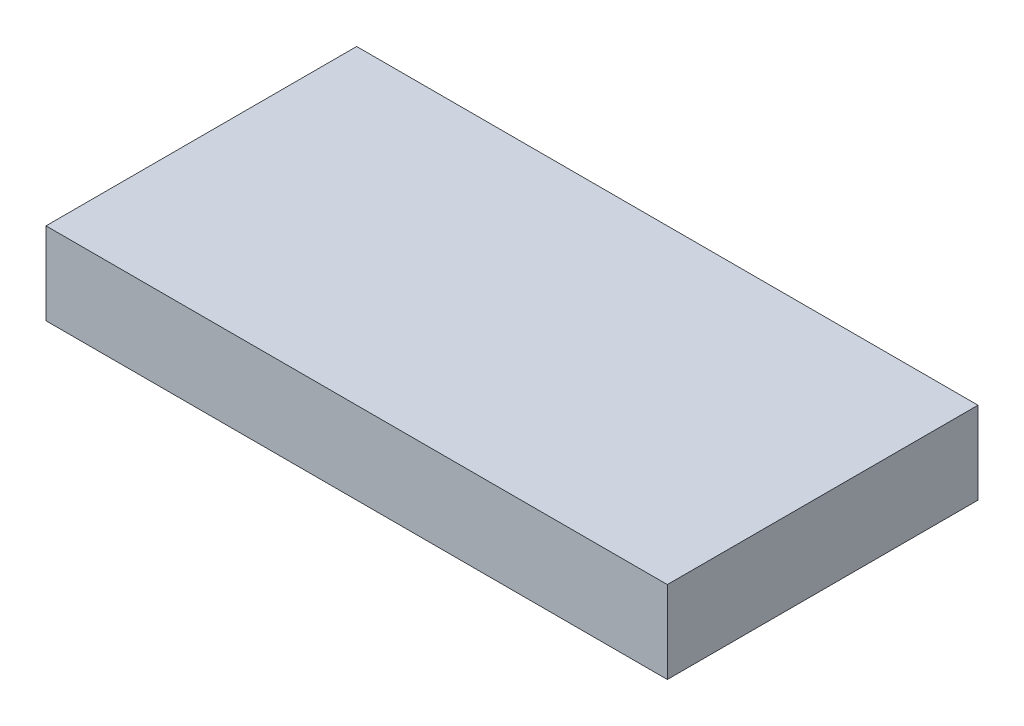
SolidWorks part; units mm, degrees
ref_plane "Front Plane" through (0, 0, 0) normal (0, 0, 1) x (1, 0, 0)
ref_plane "Top Plane" through (0, 0, 0) normal (0, 1, 0) x (1, 0, 0)
ref_plane "Right Plane" through (0, 0, 0) normal (1, 0, 0) x (0, 0, -1)
sketch "Sketch1" plane through (0, 0, 0) normal (0, 1, 0) x (1, 0, 0)
  line L1 (-215.9, -107.95) -> (215.9, -107.95)
  line L2 (-215.9, -107.95) -> (-215.9, 107.95)
  line L3 (-215.9, 107.95) -> (215.9, 107.95)
  line L4 (215.9, -107.95) -> (215.9, 107.95)
  line L5 (-215.9, -107.95) -> (215.9, 107.95) construction
  line L6 (-215.9, 107.95) -> (215.9, -107.95) construction
  point P0 (0, 0)
  dimension "D1" = 215.9
  dimension "D2" = 431.8
extrude "Boss-Extrude1" add sketch "Sketch1" along normal blind 57.15
sketch "Sketch2" plane through (0, 0, 0) normal (0, -1, 0) x (1, 0, 0)
  line L1 (-177.8, -69.85) -> (177.8, -69.85) construction
  line L2 (-177.8, -69.85) -> (-177.8, 69.85) construction
  line L3 (-177.8, 69.85) -> (177.8, 69.85) construction
  line L4 (177.8, -69.85) -> (177.8, 69.85) construction
  line L5 (-177.8, -69.85) -> (177.8, 69.85) construction
  line L6 (-177.8, 69.85) -> (177.8, -69.85) construction
  line L8 (215.9, 107.95) -> (215.9, -107.95) construction
  line L9 (-215.9, 107.95) -> (215.9, 107.95) construction
  circle A0 centre (-177.8, 69.85) radius 25.4
  circle A1 centre (-177.8, -69.85) radius 25.4
  circle A2 centre (177.8, -69.85) radius 25.4
  circle A3 centre (177.8, 69.85) radius 25.4
  point P8 (0, 0)
  dimension "D1" = 50.8
  dimension "D2" = 38.1
  dimension "D4" = 38.1
extrude "Boss-Extrude2" add sketch "Sketch2" along normal blind 3.175
equation "\"D4@Sketch2\"=\"D2@Sketch2\""
